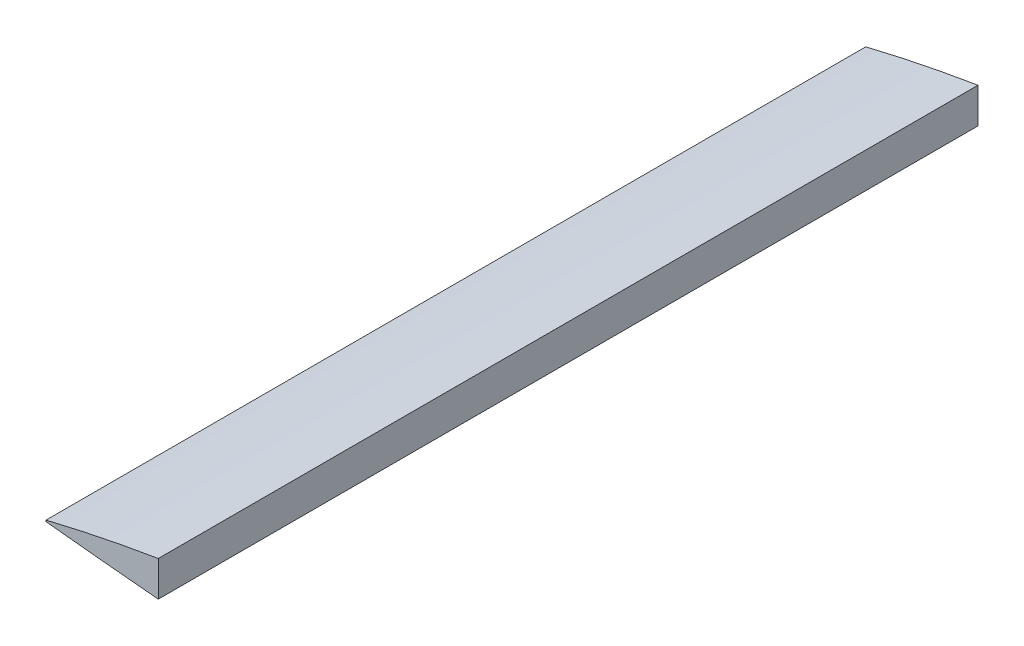
SolidWorks part; units mm, degrees
ref_plane "Front Plane" through (0, 0, 0) normal (0, 0, 1) x (1, 0, 0)
ref_plane "Top Plane" through (0, 0, 0) normal (0, 1, 0) x (1, 0, 0)
ref_plane "Right Plane" through (0, 0, 0) normal (1, 0, 0) x (0, 0, -1)
sketch "Sketch1" plane through (0, 0, 0) normal (0, 0, 1) x (1, 0, 0)
  line L0 (-238.5264, 17.5878) -> (-238.5264, -8.7167)
  line L1 (-322.333, 0.5148) -> (-322.333, -0.5066)
  spline S0 degree 3 poles (-238.5264, 17.5878) (-240.9741, 17.1819) (-246.9298, 16.1941) (-256.1812, 14.5461) (-266.0707, 12.7093) (-275.3065, 10.9116) (-283.8343, 9.1839) (-291.6033, 7.5511) (-298.5679, 6.0388) (-304.6872, 4.6711) (-309.9259, 3.4706) (-314.2535, 2.4578) (-317.6452, 1.6505) (-320.0818, 1.0631) (-321.538, 0.709) (-322.1805, 0.552) (-322.333, 0.5148) knots 0 0 0 0 0.087007 0.211705 0.329527 0.439741 0.541661 0.634652 0.718135 0.791585 0.85454 0.906603 0.947445 0.976805 0.994497 1 1 1 1
  spline S1 degree 3 poles (-238.5264, -8.7167) (-240.6457, -8.5246) (-246.2789, -8.0139) (-255.2335, -7.1819) (-265.179, -6.245) (-274.4894, -5.3529) (-283.1057, -4.5145) (-290.9725, -3.7372) (-298.0392, -3.0286) (-304.2602, -2.3953) (-309.5949, -1.8468) (-314.0082, -1.3828) (-317.4721, -1.0277) (-319.9612, -0.741) (-321.4641, -0.6201) (-322.142, -0.5059) (-322.3217, -0.5065) (-322.333, -0.5066) knots 0 0 0 0 0.075811 0.201508 0.320388 0.431695 0.534719 0.628797 0.713321 0.78774 0.851567 0.90438 0.945827 0.975633 0.993597 0.999599 1 1 1 1
extrude "Boss-Extrude1" add sketch "Sketch1" along normal blind 612
ref_plane "Plane1" through (0, 0, 83.9) normal (0, 0, 1) x (1, 0, 0)
sketch "Sketch2" plane through (0, 0, 83.9) normal (0, 0, 1) x (1, 0, 0)
  line L0 (-262.25, -9.09) -> (-241.25, -9.09)
  line L1 (-241.25, -9.09) -> (-241.25, 2.41)
  line L2 (-241.25, 2.41) -> (-262.25, 2.41)
  line L3 (-262.25, 2.41) -> (-262.25, -9.09)
extrude "Cut-Extrude1" cut sketch "Sketch2" along normal blind 13
